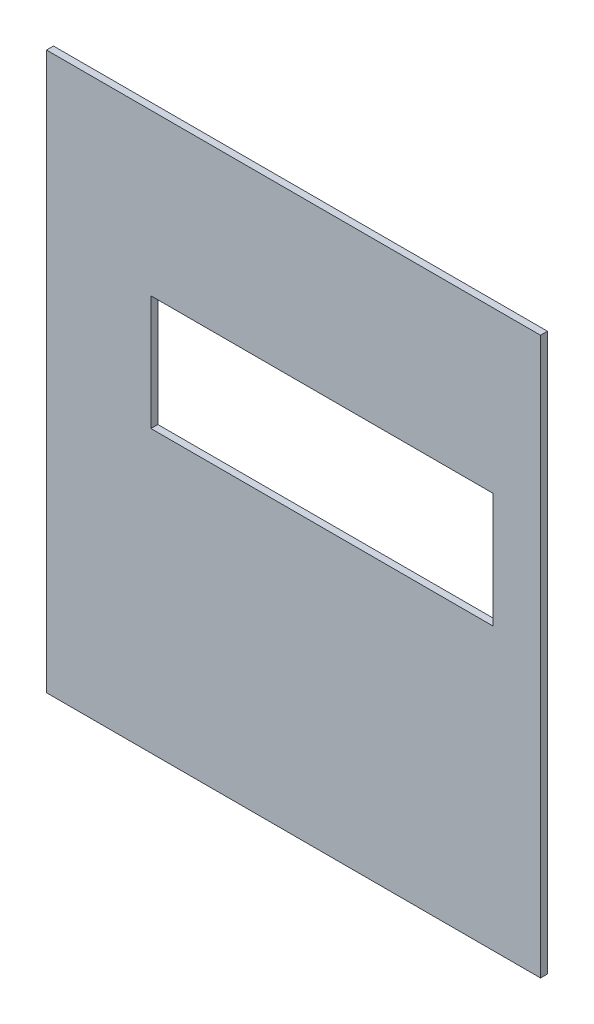
SolidWorks part; units mm, degrees
ref_plane "Plan de face" through (0, 0, 0) normal (0, 0, 1) x (1, 0, 0)
ref_plane "Plan de dessus" through (0, 0, 0) normal (0, 1, 0) x (1, 0, 0)
ref_plane "Plan de droite" through (0, 0, 0) normal (1, 0, 0) x (0, 0, -1)
sketch "Esquisse1" plane through (0, 0, 0) normal (0, 0, 1) x (1, 0, 0)
  line L1 (-177.5, 200) -> (177.5, 200)
  line L2 (-177.5, 200) -> (-177.5, -200)
  line L3 (-177.5, -200) -> (177.5, -200)
  line L4 (177.5, 200) -> (177.5, -200)
  line L5 (-177.5, 200) -> (177.5, -200) construction
  line L6 (-177.5, -200) -> (177.5, 200) construction
  point P0 (0, 0)
  dimension "D1" = 355
  dimension "D2" = 400
extrude "Boss.-Extru.1" add sketch "Esquisse1" along normal blind 5
sketch "Esquisse2" plane through (0, 0, 5) normal (0, 0, 1) x (1, 0, 0)
  line L1 (144.0456, 64.43) -> (-103.147, 64.43)
  line L2 (144.0456, 64.43) -> (144.0456, -35.57)
  line L3 (144.0456, -35.57) -> (-103.147, -35.57)
  line L4 (-103.147, 64.43) -> (-103.147, -35.57)
  dimension "D1" = 100
sketch "Esquisse6" plane through (0, 0, 5) normal (0, 0, 1) x (1, 0, 0)
  line L1 (143.5, 84.5638) -> (-102.5, 84.5638)
  line L2 (143.5, 84.5638) -> (143.5, 1.962)
  line L3 (143.5, 1.962) -> (-102.5, 1.962)
  line L4 (-102.5, 84.5638) -> (-102.5, 1.962)
extrude "Enlèv. mat.-Extru.4" cut sketch "Esquisse6" against normal through all
